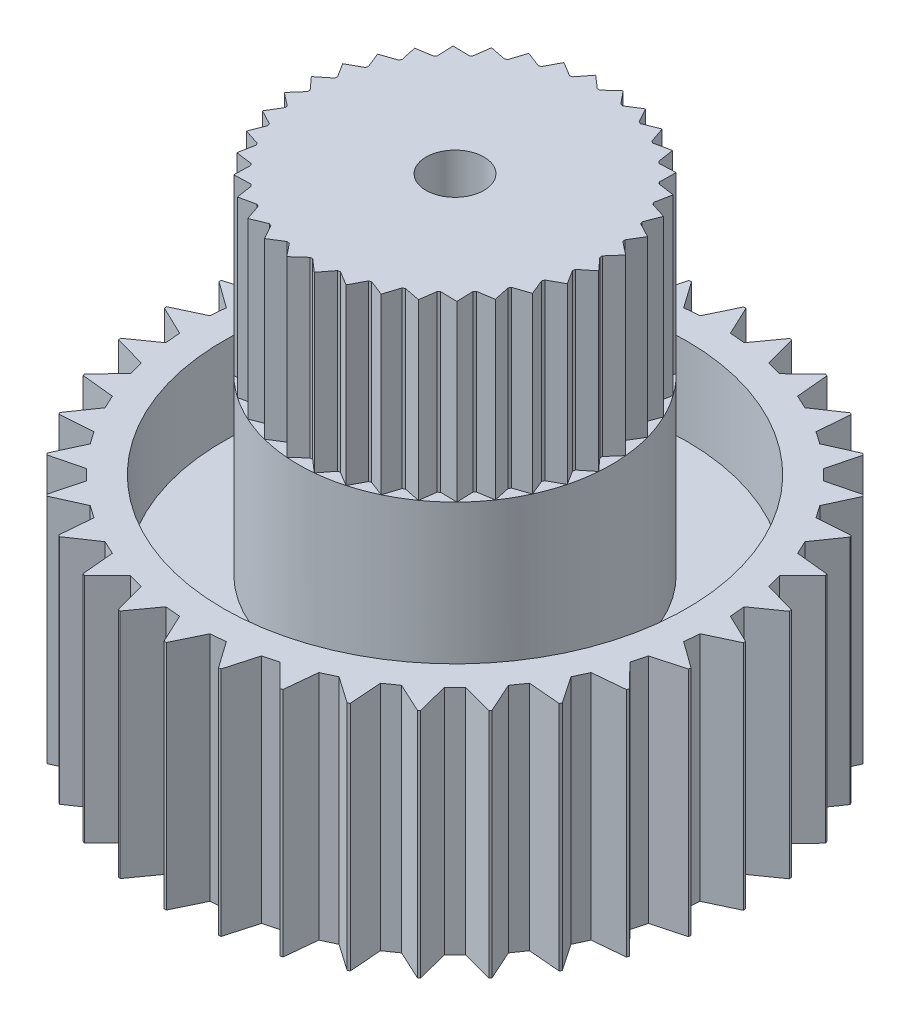
SolidWorks part; units mm, degrees
ref_plane "Front Plane" through (0, 0, 0) normal (0, 0, 1) x (1, 0, 0)
ref_plane "Top Plane" through (0, 0, 0) normal (0, 1, 0) x (1, 0, 0)
ref_plane "Right Plane" through (0, 0, 0) normal (1, 0, 0) x (0, 0, -1)
sketch "Sketch2" plane through (0, 0, 0) normal (0, 1, 0) x (1, 0, 0)
  circle A0 centre (0, 0) radius 5
extrude "Boss-Extrude1" add sketch "Sketch2" along normal blind 4
sketch "Sketch3" plane through (0, 4, 0) normal (0, 1, 0) x (1, 0, 0)
  line L0 (0, 0) -> (0, 5.8828) construction
  line L1 (0, 0) -> (0.4167, 7.1541) construction
  line L2 (0, 0) -> (0.6915, 5.9163) construction
  line L3 (0, 0) -> (1.1608, 6.5832) construction
  circle A0 centre (0, 0) radius 4.5
  dimension "D1" = 3.333
  dimension "D2" = 3.333
  dimension "D3" = 3.333
sketch "Sketch4" plane through (0, 4, 0) normal (0, 1, 0) x (1, 0, 0)
  line L0 (0.2617, 4.4924) -> (0, 5.0489)
  line L1 (0, 0) -> (0.4167, 7.1541) construction
  line L3 (0, 0) -> (0, 5.8828) construction
  line L5 (0, 5.0489) -> (0.8741, 4.9574)
  line L6 (0, 0) -> (0.6915, 5.9163) construction
  line L7 (0.5224, 4.4696) -> (0.2617, 4.4924)
  line L8 (0, 0) -> (1.1608, 6.5832) construction
  line L9 (0.8741, 4.9574) -> (0.5224, 4.4696)
  circle A0 centre (0, 0) radius 4.5 construction
extrude "Cut-Extrude1" cut sketch "Sketch4" against normal through all
sketch "Sketch5" plane through (0, 0, 0) normal (1, 0, 0) x (0, 0, -1)
  line L0 (0, 0) -> (0, 2.2331) construction
pattern_circular "CirPattern1" count 36 over 360 about axis through (0, 0, 0) along (0, 1, 0) of "Cut-Extrude1"
sketch "Sketch6" plane through (0, 4, 0) normal (0, 1, 0) x (1, 0, 0)
  circle A0 centre (0, 0) radius 4
extrude "Cut-Extrude2" cut sketch "Sketch6" against normal blind 1.5
sketch "Sketch7" plane through (0, 4, 0) normal (0, 1, 0) x (1, 0, 0)
  circle A0 centre (0, 0) radius 0.5
extrude "Cut-Extrude3" cut sketch "Sketch7" against normal through all
sketch "Sketch8" plane through (0, 0, 0) normal (0, -1, 0) x (-1, 0, 0)
  circle A0 centre (0, 0) radius 4
  circle A1 centre (0, 0) radius 1
extrude "Cut-Extrude4" cut sketch "Sketch8" against normal blind 1.5
sketch "Sketch9" plane through (0, 2.5, 0) normal (0, 1, 0) x (1, 0, 0)
  circle A0 centre (0, 0) radius 2.5
extrude "Boss-Extrude2" add sketch "Sketch9" along normal blind 6
sketch "Sketch10" plane through (0, 8.5, 0) normal (0, 1, 0) x (1, 0, 0)
  circle A0 centre (0, 0) radius 0.5
extrude "Cut-Extrude5" cut sketch "Sketch10" against normal through all
sketch "Sketch11" plane through (0, 8.5, 0) normal (0, 1, 0) x (1, 0, 0)
  circle A0 centre (0, 0) radius 2.7
sketch "Sketch12" plane through (0, 8.5, 0) normal (0, 1, 0) x (1, 0, 0)
  line L0 (0, 0) -> (6.5122, 0) construction
  line L1 (0, 0) -> (6.5292, -0.5139) construction
  line L2 (0, 0) -> (6.0238, -0.9541) construction
  line L3 (2.4692, -0.3911) -> (2.6917, -0.2118)
  line L4 (2.6917, -0.2118) -> (2.5, 0)
  line L5 (2.5, 0) -> (2.4692, -0.3911)
  circle A0 centre (0, 0) radius 2.5 construction
  circle A1 centre (0, 0) radius 2.7 construction
  dimension "D1" = 4.5
  dimension "D2" = 4.5
extrude "Boss-Extrude3" add sketch "Sketch12" against normal blind 3
pattern_circular "CirPattern2" count 36 every 10 about axis through (0, 0, 0) along (0, 1, 0) of "Boss-Extrude3"
sketch "Sketch13" plane through (0, 2.5, 0) normal (0, 1, 0) x (1, 0, 0)
  circle A0 centre (0, 0) radius 2.7
extrude "Boss-Extrude4" add sketch "Sketch13" along normal blind 3
